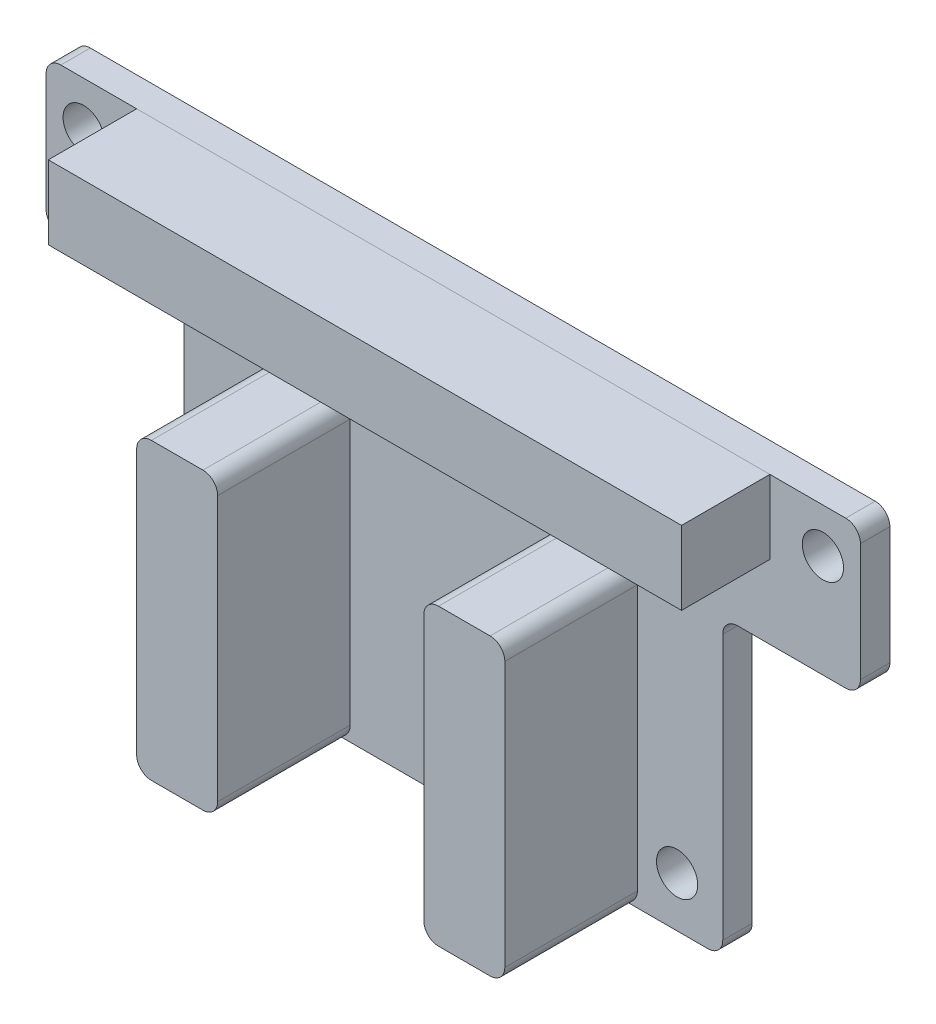
SolidWorks part; units mm, degrees
ref_plane "前视基准面" through (0, 0, 0) normal (0, 0, 1) x (1, 0, 0)
ref_plane "上视基准面" through (0, 0, 0) normal (0, 1, 0) x (1, 0, 0)
ref_plane "右视基准面" through (0, 0, 0) normal (1, 0, 0) x (0, 0, -1)
sketch "草图1" plane through (0, 0, 0) normal (0, 0, 1) x (1, 0, 0)
  line L1 (-27.65, 5) -> (27.65, 5)
  line L2 (-27.65, 5) -> (-27.65, -5)
  line L3 (-27.65, -5) -> (27.65, -5)
  line L4 (27.65, 5) -> (27.65, -5)
  line L5 (0, -5) -> (0, 5) construction
  line L6 (-27.65, 0) -> (27.65, 0) construction
  line L7 (-18.3, -25) -> (18.3, -25)
  line L8 (-18.3, -25) -> (-18.3, -5)
  line L9 (-18.3, -5) -> (18.3, -5)
  line L10 (18.3, -25) -> (18.3, -5)
  line L11 (0, -5) -> (0, -25) construction
  line L12 (-18.3, -15) -> (18.3, -15) construction
  point P0 (0, 0)
  point P4 (0, -15)
  dimension "D1" = 55.3
  dimension "D2" = 36.6
  dimension "D3" = 10
  dimension "D4" = 30
extrude "凸台-拉伸1" add sketch "草图1" along normal blind 2 contours L4 L1 L2 L3 | L7 L10 L3 L8
fillet "圆角1" radius 1 8 edges at (27.65, -5, 1) (18.3, -5, 1) (18.3, -25, 1) (-18.3, -5, 1) (-27.65, -5, 1) (-27.65, 5, 1) (27.65, 5, 1) (-18.3, -25, 1)
sketch "草图2" plane through (0, 0, 2) normal (0, 0, 1) x (1, 0, 0)
  line L2 (-26.65, 5) -> (26.65, 5) construction
  line L3 (0, 11.9797) -> (0, -28.659) construction
  circle A0 centre (-25.1, 2) radius 1.4
  circle A1 centre (-15.2, -21.6) radius 1.4
  circle A2 centre (15.2, -21.6) radius 1.4
  circle A3 centre (25.1, 2) radius 1.4
  dimension "D1" = 2.8
  dimension "D2" = 1.6
  dimension "D3" = 27.6
  dimension "D4" = 28
  dimension "D5" = 53
extrude "切除-拉伸1" cut sketch "草图2" against normal blind 2
sketch "草图3" plane through (0, 0, 2) normal (0, 0, 1) x (1, 0, 0)
  line L0 (0, 10.085) -> (0, -29.5529) construction
  line L1 (-17.3, -25) -> (17.3, -25) construction
  line L2 (-12.5, -25) -> (-7, -25)
  line L3 (-12.5, -25) -> (-12.5, -5)
  line L4 (-12.5, -5) -> (-7, -5)
  line L5 (-7, -25) -> (-7, -5)
  line L6 (7, -25) -> (7, -5)
  line L7 (12.5, -5) -> (7, -5)
  line L8 (12.5, -25) -> (12.5, -5)
  line L9 (12.5, -25) -> (7, -25)
  dimension "D1" = 20
  dimension "D2" = 14
  dimension "D3" = 25
extrude "凸台-拉伸2" add sketch "草图3" along normal blind 9 separate body
fillet "圆角2" radius 1 4 edges at (-12.5, -5, 6.5) (-7, -5, 6.5) (-12.5, -25, 6.5) (-7, -25, 6.5)
fillet "圆角3" radius 1 4 edges at (7, -5, 6.5) (12.5, -5, 6.5) (12.5, -25, 6.5) (7, -25, 6.5)
sketch "草图4" plane through (0, 0, 0) normal (0, 0, -1) x (-1, 0, 0)
  line L0 (0, 3.789) -> (0, -23.0796) construction
  line L1 (26.65, 5) -> (-26.65, 5) construction
  line L2 (-12.5, -4) -> (-7, -4)
  line L3 (-12.5, -4) -> (-12.5, -17)
  line L4 (-12.5, -17) -> (-7, -17)
  line L5 (-7, -4) -> (-7, -17)
  line L6 (17.3, -25) -> (-17.3, -25) construction
  line L7 (7, -4) -> (7, -17)
  line L8 (12.5, -17) -> (7, -17)
  line L9 (12.5, -4) -> (12.5, -17)
  line L10 (12.5, -4) -> (7, -4)
  dimension "D1" = 14
  dimension "D2" = 25
  dimension "D3" = 9
  dimension "D4" = 8
extrude "凸台-拉伸3" add sketch "草图4" along normal blind 2 separate body
sketch "草图5" plane through (0, 0, 2) normal (0, 0, -1) x (-1, 0, 0)
  line L0 (26.65, 5) -> (-26.65, 5) construction
  line L1 (21.5, 0) -> (-21.5, 0)
  line L2 (21.5, 0) -> (21.5, 5)
  line L3 (21.5, 5) -> (-21.5, 5)
  line L4 (-21.5, 0) -> (-21.5, 5)
  line L5 (0, 5) -> (0, 0) construction
  line L6 (21.5, 2.5) -> (-21.5, 2.5) construction
  point P0 (0, 2.5)
  dimension "D1" = 43
  dimension "D2" = 5
extrude "凸台-拉伸4" add sketch "草图5" against normal blind 6 separate body
